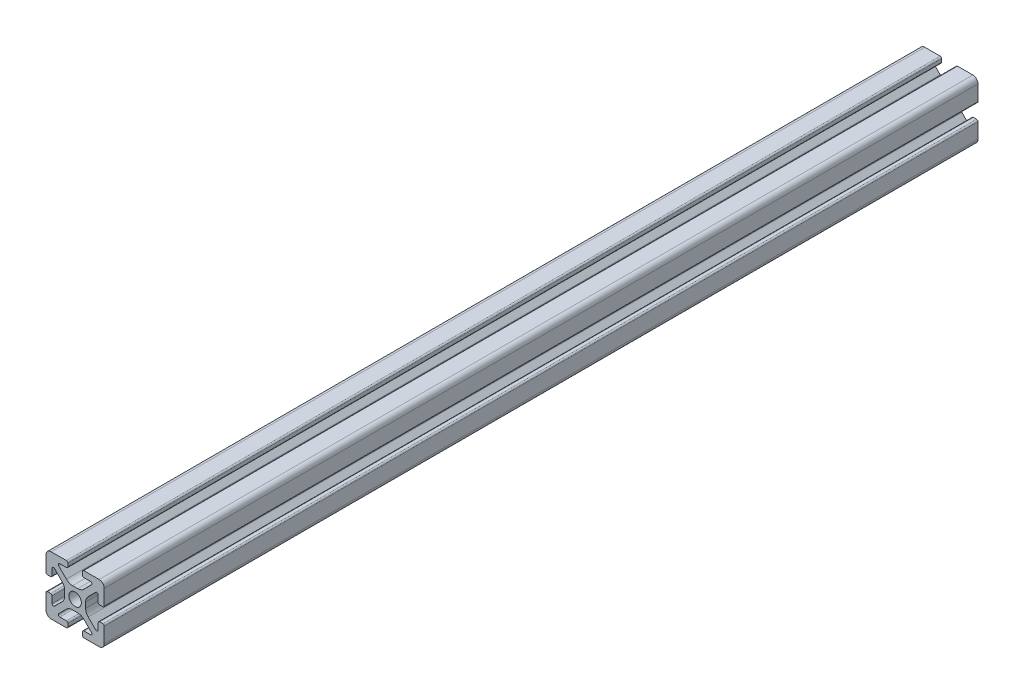
SolidWorks part; units mm, degrees
ref_plane "Front Plane" through (0, 0, 0) normal (0, 0, 1) x (1, 0, 0)
ref_plane "Top Plane" through (0, 0, 0) normal (0, 1, 0) x (1, 0, 0)
ref_plane "Right Plane" through (0, 0, 0) normal (1, 0, 0) x (0, 0, -1)
sketch "Sketch2" plane through (0, 0, 0) normal (0, 0, 1) x (1, 0, 0)
  line L0 (0, 10) -> (0, -10) construction
  line L1 (-10, 0) -> (10, 0) construction
  line L2 (2.5, -10) -> (10, -10)
  line L3 (10, -10) -> (10, -2.5)
  line L4 (2.5, -10) -> (2.5, -7.9246)
  line L5 (2.5, -7.9246) -> (6.4571, -7.9246)
  line L6 (6.4571, -7.9246) -> (2.1325, -3.6)
  line L7 (0, 0) -> (10, -10) construction
  line L8 (10, -2.5) -> (7.9246, -2.5)
  line L9 (7.9246, -2.5) -> (7.9246, -6.4571)
  line L10 (7.9246, -6.4571) -> (3.6, -2.1325)
  line L11 (5.7623, -4.2948) -> (4.2948, -5.7623) construction
  circle A0 centre (0, 0) radius 2.15
  arc A1 (5.25, -7.9246) -> (5.6036, -7.0711) centre (5.25, -7.4246) ccw construction
  point P8 (0, -3.6)
  point P16 (5.0286, -5.0286)
  dimension "Center Hole Diameter" = 4.3
  dimension "D3" = 0.5
  dimension "Rail Height" = 20
  dimension "Rail Width" = 20
  dimension "T-Slot Width" = 5
  dimension "Slot Depth" = 6.4
  dimension "Slot Inner Width" = 11.5
sketch "Sketch3" plane through (0, 0, 0) normal (1, 0, 0) x (0, 0, -1)
  line L0 (-150, -10) -> (150, -10) construction
  line L1 (-124.6, 0) -> (124.6, 0) construction
  line L2 (0, 10) -> (0, -10) construction
  line L3 (0, 10) -> (0, -10) construction
  point P6 (-124.6, 0)
  point P8 (124.6, 0)
  dimension "Length" = 300
  dimension "D1" = 25.4
sketch "Sketch4" plane through (0, 0, 0) normal (0, 0, 1) x (1, 0, 0)
  line L0 (3, -10) -> (8.25, -10)
  line L1 (2.5, -10) -> (10, -10) construction
  line L2 (2.5, -10) -> (2.5, -7.9246) construction
  line L3 (2.5, -7.9246) -> (6.4571, -7.9246) construction
  line L4 (2.5, -8.4246) -> (2.5, -9.5)
  line L5 (3, -7.9246) -> (5.25, -7.9246)
  line L6 (0, -3.6) -> (0.8898, -3.6)
  line L7 (6.4571, -7.9246) -> (2.1325, -3.6) construction
  line L8 (3.0112, -4.4787) -> (5.6036, -7.0711)
  line L9 (10, -10) -> (10, -2.5) construction
  line L10 (7.9246, -6.4571) -> (3.6, -2.1325) construction
  line L11 (7.9246, -2.5) -> (7.9246, -6.4571) construction
  line L12 (7.9246, -5.25) -> (7.9246, -3)
  line L13 (10, -2.5) -> (7.9246, -2.5) construction
  line L14 (8.4246, -2.5) -> (9.5, -2.5)
  line L15 (10, -3) -> (10, -8.25)
  line L16 (7.0711, -5.6036) -> (4.4787, -3.0112)
  line L17 (3.6, 0) -> (3.6, -0.8898)
  line L18 (-10, 0) -> (10, 0) construction
  line L19 (0, -3.6) -> (0, -2.15)
  line L20 (0, 10) -> (0, -10) construction
  line L21 (3.6, 0) -> (2.15, 0)
  arc A0 (2.5, -9.5) -> (3, -10) centre (3, -9.5) ccw
  arc A1 (5.25, -7.9246) -> (5.6036, -7.0711) centre (5.25, -7.4246) ccw construction
  arc A2 (2.5, -8.4246) -> (3, -7.9246) centre (3, -8.4246) cw
  arc A3 (5.25, -7.9246) -> (5.6036, -7.0711) centre (5.25, -7.4246) ccw
  arc A4 (0.8898, -3.6) -> (3.0112, -4.4787) centre (0.8898, -6.6) cw
  arc A5 (8.25, -10) -> (10, -8.25) centre (8.25, -8.25) ccw
  arc A6 (7.0711, -5.6036) -> (7.9246, -5.25) centre (7.4246, -5.25) ccw
  arc A7 (7.9246, -3) -> (8.4246, -2.5) centre (8.4246, -3) cw
  arc A8 (9.5, -2.5) -> (10, -3) centre (9.5, -3) cw
  arc A9 (4.4787, -3.0112) -> (3.6, -0.8898) centre (6.6, -0.8898) cw
  circle A10 centre (0, 0) radius 2.15 construction
  arc A11 (0, -2.15) -> (2.15, 0) centre (0, 0) ccw
  dimension "D1" = 1.75
  dimension "D2" = 3
extrude "Boss-Extrude1" add sketch "Sketch4" along normal mid plane 300
mirror "Mirror1" about plane through (0, 0, 0) normal (1, 0, 0) of bodies 134
mirror "Mirror2" about plane through (0, 0, 0) normal (0, 1, 0) of bodies 135
equation "\"D3@Sketch2\"=\"T-Slot Width@Sketch2\"*0.1"
equation "\"D1@Sketch4\"=\"D3@Sketch2\"*3.5"
equation "\"D2@Sketch4\"=\"D3@Sketch2\"*6"
equation "\"D1@Boss-Extrude1\"=\"Length@Sketch3\""
